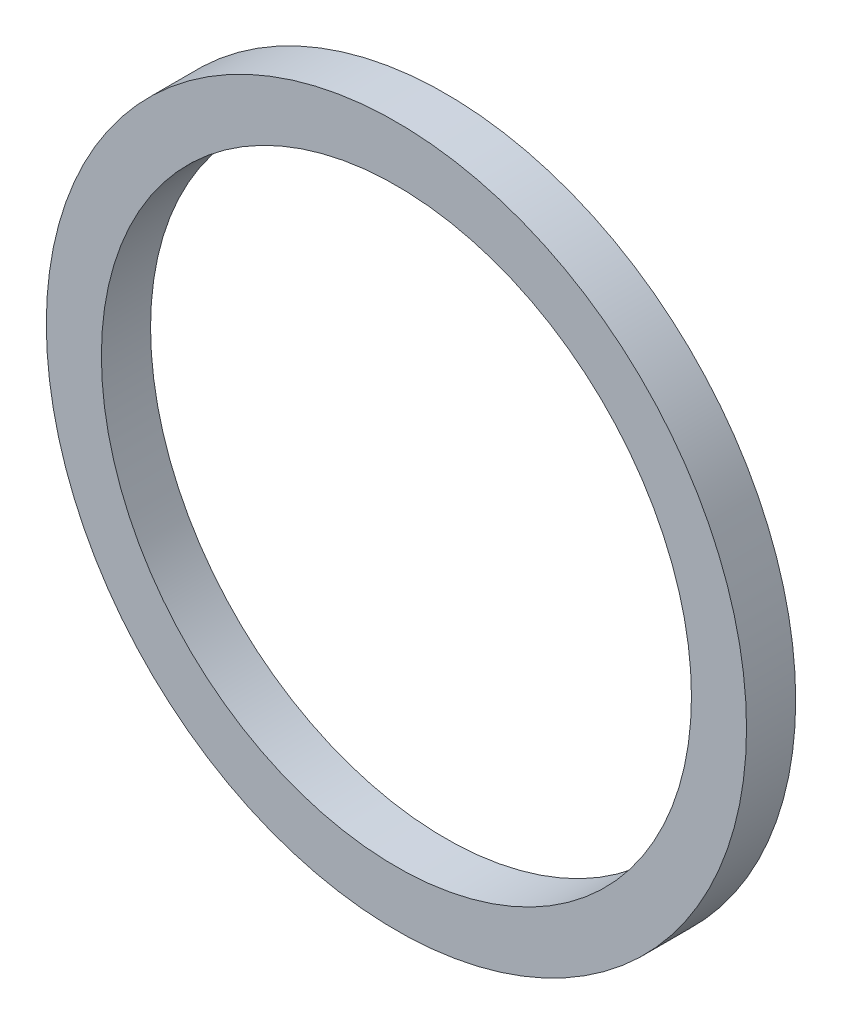
SolidWorks part; units mm, degrees
material "Plain Carbon Steel"
ref_plane "Front Plane" through (0, 0, 0) normal (0, 0, 1) x (1, 0, 0)
ref_plane "Top Plane" through (0, 0, 0) normal (0, 1, 0) x (1, 0, 0)
ref_plane "Right Plane" through (0, 0, 0) normal (1, 0, 0) x (0, 0, -1)
sketch "Sketch1" plane through (0, 0, 0) normal (0, 0, 1) x (1, 0, 0)
  circle A0 centre (0, 0) radius 22.606
  circle A1 centre (0, 0) radius 19.05
  dimension "D1" = 45.212
  dimension "D2" = 38.1
extrude "Boss-Extrude1" add sketch "Sketch1" along normal blind 3.175
